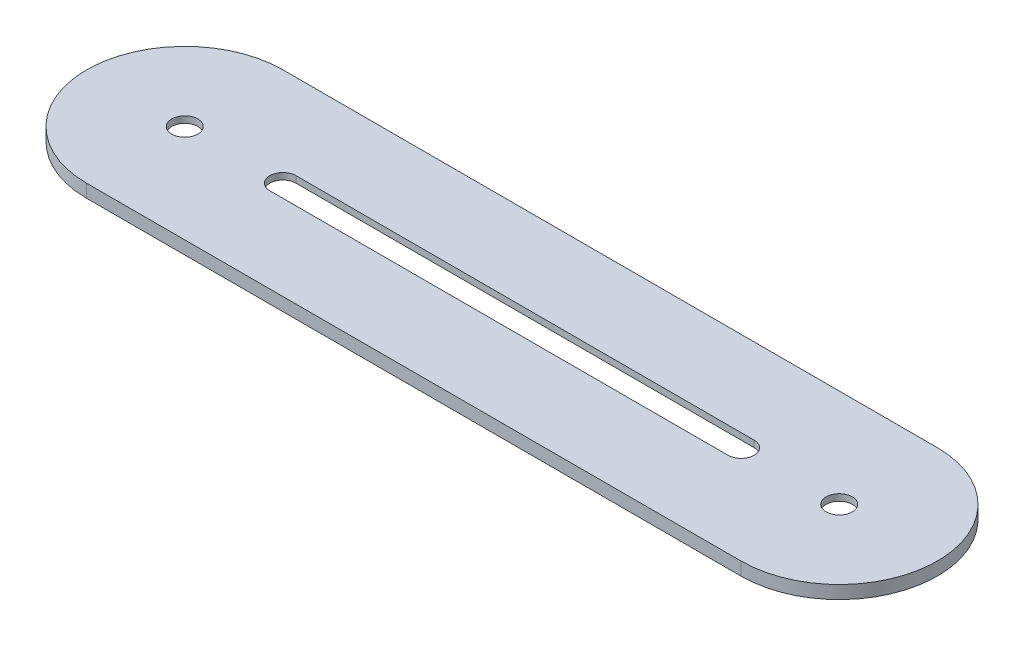
SolidWorks part; units mm, degrees
ref_plane "Front Plane" through (0, 0, 0) normal (1, 0, 0) x (0, 1, 0)
ref_plane "Top Plane" through (0, 0, 0) normal (0, 0, 1) x (0, 1, 0)
ref_plane "Right Plane" through (0, 0, 0) normal (0, 1, 0) x (-1, 0, 0)
sketch "Sketch1" plane through (0, 0, 0) normal (0, 1, 0) x (-1, 0, 0)
  line L0 (-250, 0) -> (250, 0) construction
  line L1 (-250, 75) -> (250, 75)
  line L2 (-250, -75) -> (250, -75)
  line L3 (-175, 0) -> (175, 0) construction
  line L8 (-175, 10) -> (175, 10)
  line L9 (-175, -10) -> (175, -10)
  line L10 (0, 55) -> (0, -55) construction
  arc A0 (-250, 75) -> (-250, -75) centre (-250, 0) ccw
  arc A1 (250, -75) -> (250, 75) centre (250, 0) ccw
  circle A3 centre (250, 0) radius 10
  arc A8 (-175, 10) -> (-175, -10) centre (-175, 0) ccw
  arc A9 (175, -10) -> (175, 10) centre (175, 0) ccw
  circle A10 centre (-250, 0) radius 10
  point P3 (0, 0)
  point P9 (0, 0)
  dimension "D2" = 150
  dimension "D3" = 20
  dimension "D4" = 350
  dimension "D1" = 500
extrude "Boss-Extrude1" add sketch "Sketch1" along normal mid plane 10
sketch "Sketch4" plane through (0, -5, 0) normal (0, -1, 0) x (1, 0, 0)
  line L0 (250, 72) -> (-250, 72)
  line L1 (-250, -72) -> (250, -72)
  line L2 (250, 75) -> (-250, 75)
  line L3 (-250, -75) -> (250, -75)
  line L4 (250, 75) -> (-250, 75) construction
  line L5 (-250, -75) -> (250, -75) construction
  arc A0 (-250, 72) -> (-250, -72) centre (-250, 0) ccw
  arc A1 (250, -72) -> (250, 72) centre (250, 0) ccw
  arc A2 (250, -75) -> (250, 75) centre (250, 0) ccw
  arc A3 (-250, 75) -> (-250, -75) centre (-250, 0) ccw
  arc A4 (250, -75) -> (250, 75) centre (250, 0) ccw construction
  arc A5 (-250, 75) -> (-250, -75) centre (-250, 0) ccw construction
  dimension "D1" = 0
  dimension "D2" = 3
extrude "Cut-Extrude1" cut sketch "Sketch4" against normal blind 5
